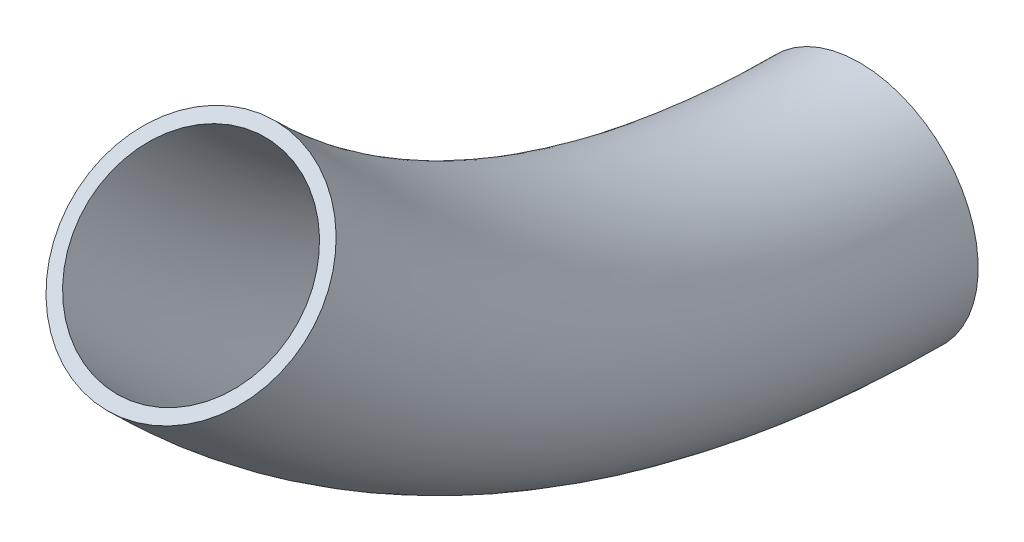
SolidWorks part; units mm, degrees
material "AISI 321 Annealed Stainless Steel (SS)"
ref_plane "Front Plane" through (0, 0, 0) normal (0, 0, 1) x (1, 0, 0)
ref_plane "Top Plane" through (0, 0, 0) normal (0, 1, 0) x (1, 0, 0)
ref_plane "Right Plane" through (0, 0, 0) normal (1, 0, 0) x (0, 0, -1)
sketch "Sketch1" plane through (0, 0, 0) normal (0, 0, 1) x (1, 0, 0)
  circle A0 centre (0, 0) radius 17.5
  circle A1 centre (0, 0) radius 15.5
  dimension "D1" = 35
  dimension "D2" = 2
sketch "Sketch2" plane through (0, 0, 0) normal (1, 0, 0) x (0, 0, -1)
  line L0 (0, 0) -> (53.5038, 0) construction
  line L1 (-124.5956, 66.73) -> (-72.97, 15.1044) construction
  arc A0 (0, 0) -> (-98.7828, 40.9172) centre (0, 139.7) cw
  dimension "D2" = 139.7
  dimension "D1" = 135
sweep "Sweep1" add profiles "Sketch1" path "Sketch2"
